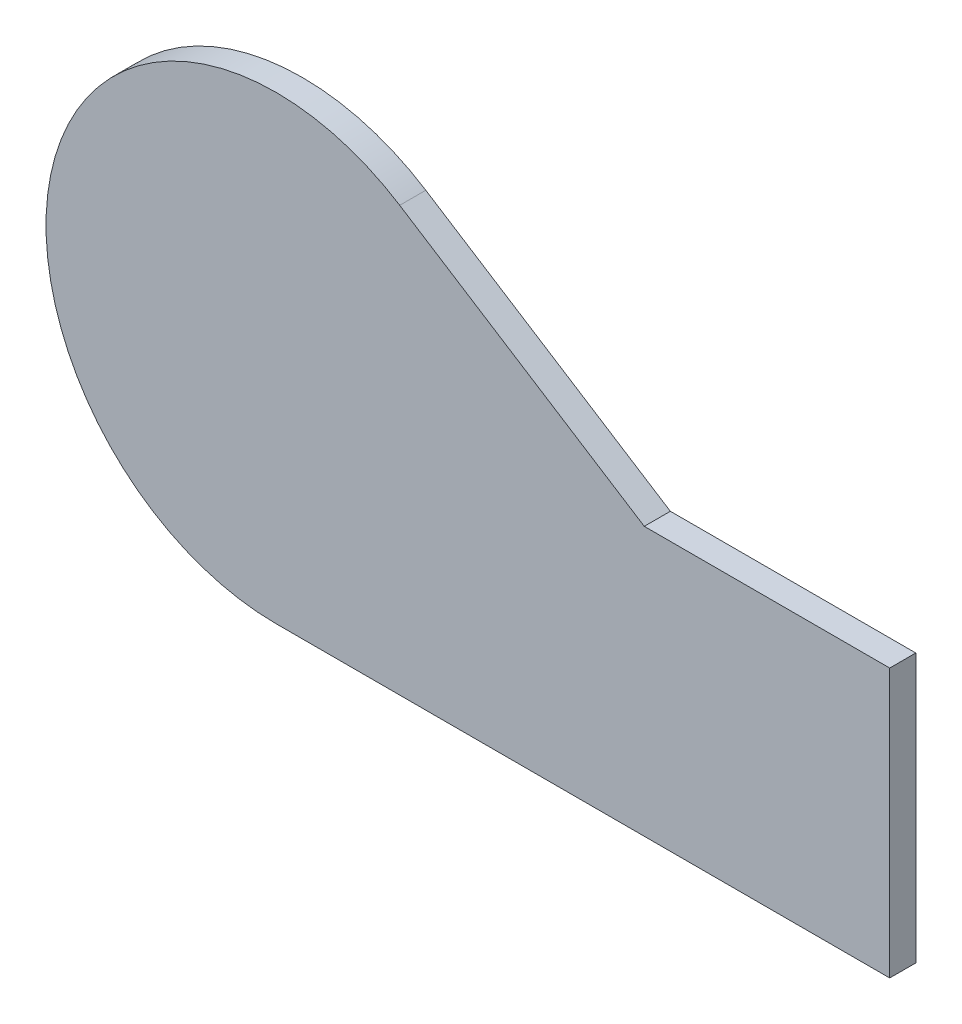
SolidWorks part; units mm, degrees
ref_plane "前视基准面" through (0, 0, 0) normal (0, 0, 1) x (1, 0, 0)
ref_plane "上视基准面" through (0, 0, 0) normal (0, 1, 0) x (1, 0, 0)
ref_plane "右视基准面" through (0, 0, 0) normal (1, 0, 0) x (0, 0, -1)
sketch "Sketch1" plane through (0, 0, 0) normal (0, 0, 1) x (1, 0, 0)
  line L0 (0, -30) -> (80, -30)
  line L1 (80, -30) -> (80, 5)
  line L2 (80, 5) -> (48, 5)
  line L4 (48, 5) -> (16.1141, 25.3049)
  arc A0 (16.1141, 25.3049) -> (0, -30) centre (0, 0) ccw
  dimension "D1" = 80
  dimension "D2" = 60
  dimension "D3" = 35
  dimension "D4" = 32
extrude "Boss-Extrude1" add sketch "Sketch1" along normal blind 3.4
sketch "Sketch2" plane through (0, 0, 3.4) normal (0, 0, 1) x (1, 0, 0)
  circle A0 centre (48, -12.5) radius 2.75
  circle A3 centre (48, -12.5) radius 2
  dimension "D2" = 5.5
